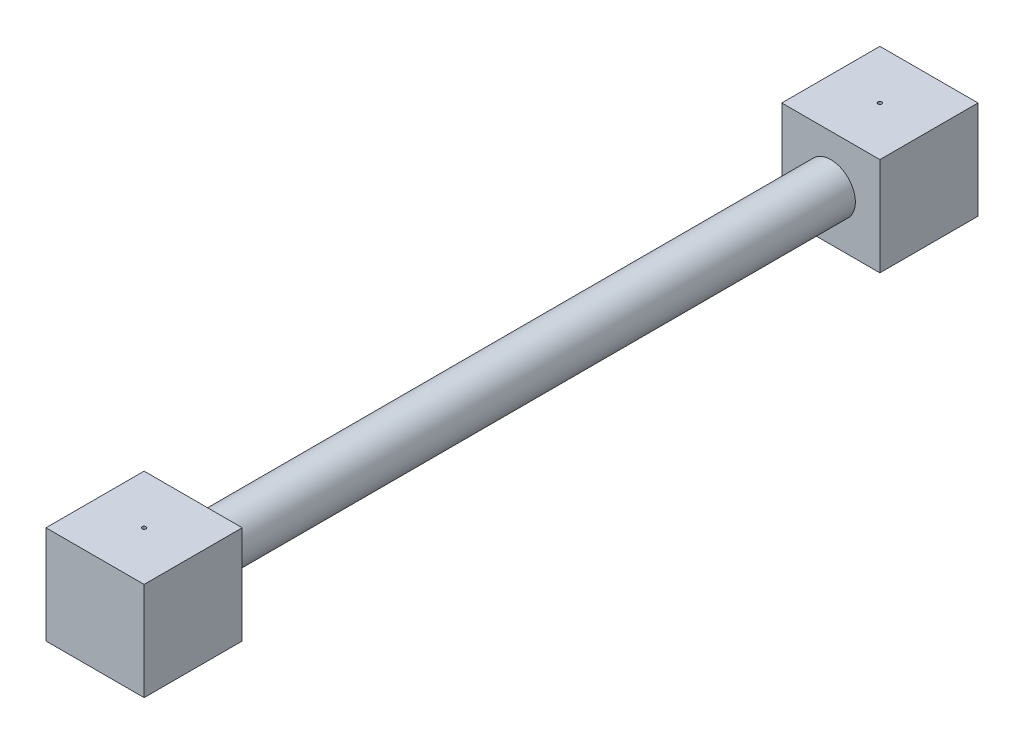
SolidWorks part; units mm, degrees
material "PVC 0.007 Plasticized"
ref_plane "Front Plane" through (0, 0, 0) normal (0, 0, 1) x (1, 0, 0)
ref_plane "Top Plane" through (0, 0, 0) normal (0, 1, 0) x (1, 0, 0)
ref_plane "Right Plane" through (0, 0, 0) normal (1, 0, 0) x (0, 0, -1)
sketch "Sketch3" plane through (0, 0, 0) normal (0, 0, 1) x (1, 0, 0)
  circle A0 centre (0, 0) radius 12.7
  dimension "D1" = 25.4
extrude "Boss-Extrude1" add sketch "Sketch3" along normal blind 381
sketch "Sketch4" plane through (0, 0, 0) normal (0, 0, -1) x (-1, 0, 0)
  line L1 (-25.4, -25.4) -> (25.4, -25.4)
  line L2 (-25.4, -25.4) -> (-25.4, 25.4)
  line L3 (-25.4, 25.4) -> (25.4, 25.4)
  line L4 (25.4, -25.4) -> (25.4, 25.4)
  line L5 (-25.4, -25.4) -> (25.4, 25.4) construction
  line L6 (-25.4, 25.4) -> (25.4, -25.4) construction
  point P0 (0, 0)
  dimension "D1" = 50.8
  dimension "D2" = 50.8
extrude "Boss-Extrude2" add sketch "Sketch4" along normal mid plane 50.8
sketch "Sketch5" plane through (0, 0, 381) normal (0, 0, 1) x (1, 0, 0)
  line L1 (-25.4, -25.4) -> (25.4, -25.4)
  line L2 (-25.4, -25.4) -> (-25.4, 25.4)
  line L3 (-25.4, 25.4) -> (25.4, 25.4)
  line L4 (25.4, -25.4) -> (25.4, 25.4)
  line L5 (-25.4, -25.4) -> (25.4, 25.4) construction
  line L6 (-25.4, 25.4) -> (25.4, -25.4) construction
  point P0 (0, 0)
extrude "Boss-Extrude3" add sketch "Sketch5" along normal mid plane 50.8
sketch "Sketch6" plane through (0, 25.4, 0) normal (0, 1, 0) x (1, 0, 0)
  circle A0 centre (0, -381) radius 1.016
  circle A1 centre (0, 0) radius 0.9922
  dimension "D1" = 1.9844
  dimension "D2" = 2.032
extrude "Cut-Extrude1" cut sketch "Sketch6" against normal through all
